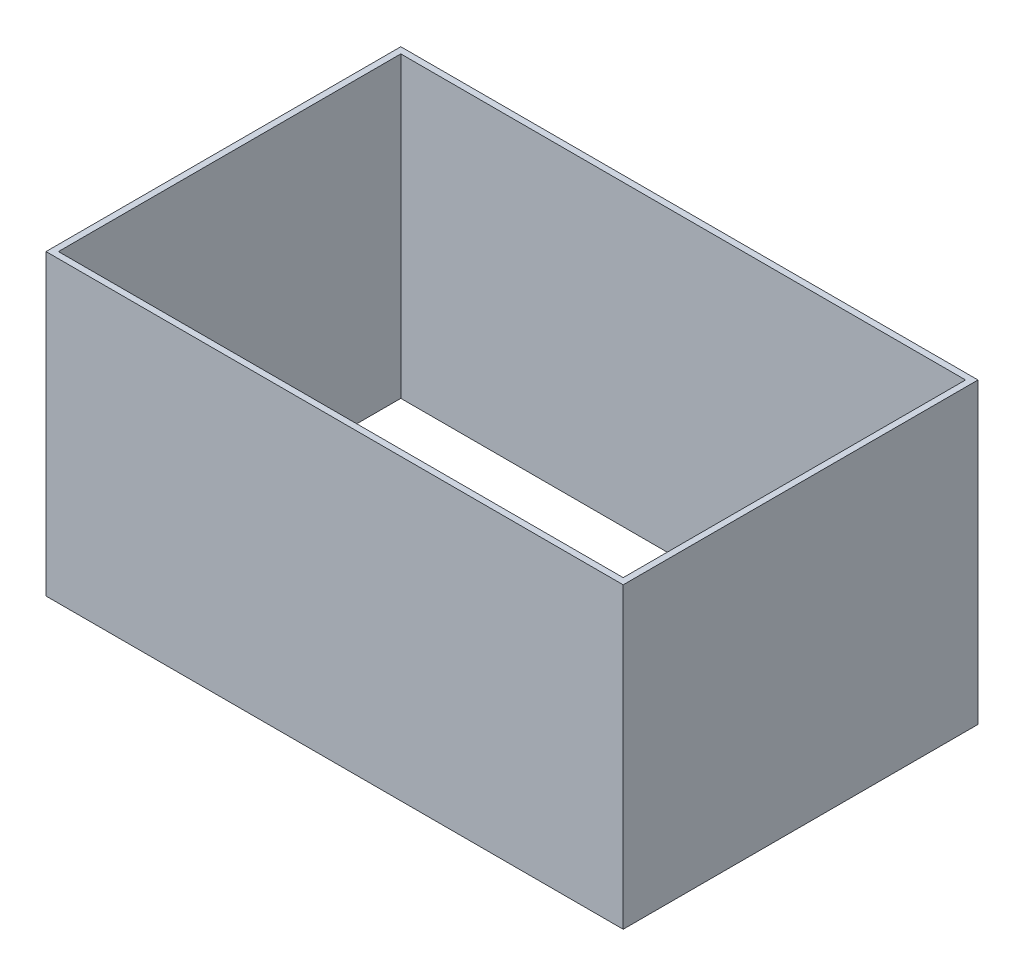
SolidWorks part; units mm, degrees
ref_plane "Front Plane" through (0, 0, 0) normal (0, 0, 1) x (1, 0, 0)
ref_plane "Top Plane" through (0, 0, 0) normal (0, 1, 0) x (1, 0, 0)
ref_plane "Right Plane" through (0, 0, 0) normal (1, 0, 0) x (0, 0, -1)
sketch "Sketch1" plane through (0, 0, 0) normal (0, 1, 0) x (1, 0, 0)
  line L1 (115.4031, -69.9586) -> (-115.4031, -69.9586)
  line L2 (115.4031, -69.9586) -> (115.4031, 69.9586)
  line L3 (115.4031, 69.9586) -> (-115.4031, 69.9586)
  line L4 (-115.4031, -69.9586) -> (-115.4031, 69.9586)
  line L5 (115.4031, -69.9586) -> (-115.4031, 69.9586) construction
  line L6 (115.4031, 69.9586) -> (-115.4031, -69.9586) construction
  point P0 (0, 0)
extrude "Extrude-Thin1" add sketch "Sketch1" along normal blind 121.92 thin thin type one direction wall 2.54
